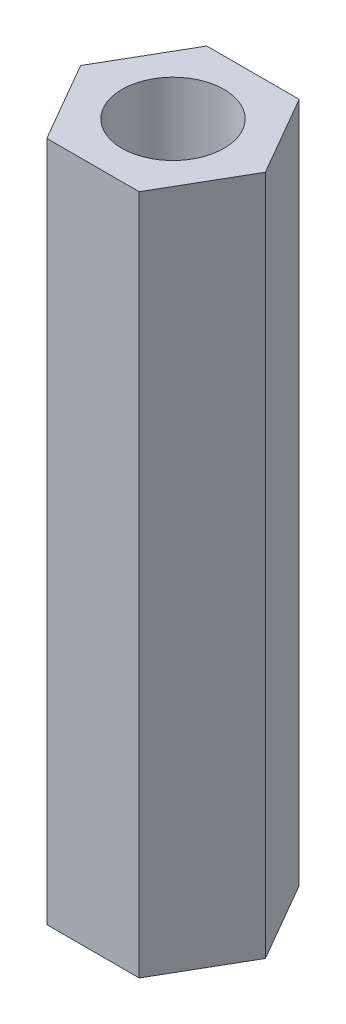
SolidWorks part; units mm, degrees
material "Brass"
ref_plane "Front Plane" through (0, 0, 0) normal (0, 0, 1) x (1, 0, 0)
ref_plane "Top Plane" through (0, 0, 0) normal (0, 1, 0) x (1, 0, 0)
ref_plane "Right Plane" through (0, 0, 0) normal (1, 0, 0) x (0, 0, -1)
sketch "Sketch1" plane through (0, 0, 0) normal (0, 1, 0) x (1, 0, 0)
  line L1 (2.7135, 0) -> (1.3568, 2.35)
  line L2 (1.3568, 2.35) -> (-1.3568, 2.35)
  line L3 (-1.3568, 2.35) -> (-2.7135, 0)
  line L4 (-2.7135, 0) -> (-1.3568, -2.35)
  line L5 (-1.3568, -2.35) -> (1.3568, -2.35)
  line L6 (1.3568, -2.35) -> (2.7135, 0)
  circle A0 centre (0, 0) radius 2.35 construction
  circle A1 centre (0, 0) radius 1.5
extrude "Boss-Extrude1" add sketch "Sketch1" along normal blind 20
